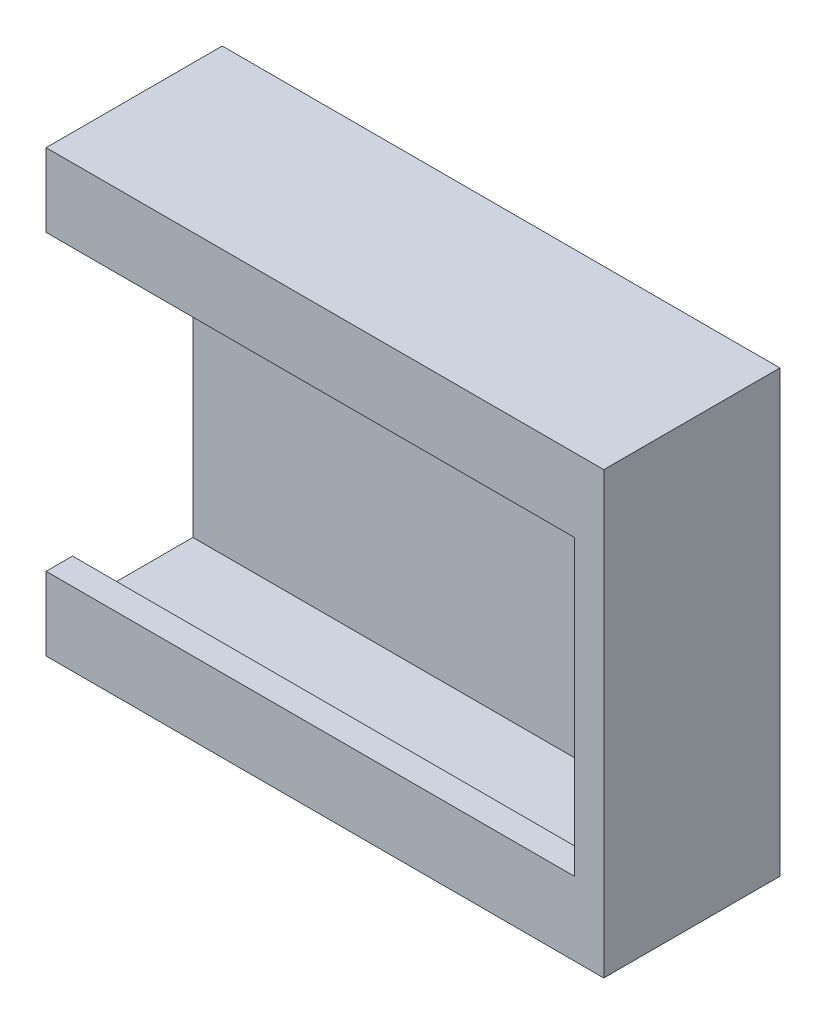
SolidWorks part; units mm, degrees
material "Alliage 1060"
ref_plane "Plan de dessus" through (0, 0, 0) normal (0, 0, 1) x (1, 0, 0)
ref_plane "Plan de droite" through (0, 0, 0) normal (0, 1, 0) x (1, 0, 0)
ref_plane "Plan de face" through (0, 0, 0) normal (1, 0, 0) x (0, 0, -1)
sketch "Esquisse1" plane through (0, 0, 0) normal (0, 0, 1) x (1, 0, 0)
  line L1 (0, 0) -> (95, 0)
  line L2 (0, 0) -> (0, 75)
  line L3 (0, 75) -> (95, 75)
  line L4 (95, 0) -> (95, 75)
  dimension "D1" = 75
  dimension "D2" = 95
extrude "Boss.-Extru.1" add sketch "Esquisse1" along normal blind 5
sketch "Esquisse2" plane through (0, 0, 5) normal (0, 0, 1) x (1, 0, 0)
  line L3 (0, 70) -> (0, 75)
  line L4 (0, 75) -> (95, 75)
  line L5 (95, 75) -> (95, 0)
  line L6 (0, 5) -> (90, 5)
  line L7 (90, 5) -> (90, 70)
  line L8 (90, 70) -> (0, 70)
  line L9 (0, 5) -> (90, 5)
  line L10 (90, 5) -> (90, 70)
  line L11 (90, 70) -> (0, 70)
  line L12 (95, 0) -> (0, 0)
  line L13 (0, 0) -> (0, 5)
  dimension "D1" = 5
extrude "Boss.-Extru.2" add sketch "Esquisse2" along normal blind 25
sketch "Esquisse3" plane through (90, 0, 0) normal (-1, 0, 0) x (0, 0, 1)
  line L1 (30, 70) -> (30, 5) construction
  line L8 (30, 70) -> (25.5, 70)
  line L9 (30, 70) -> (5, 70) construction
  line L10 (25.5, 70) -> (25.5, 62.5)
  line L11 (30, 37.5) -> (5, 37.5) construction
  line L12 (5, 70) -> (5, 5) construction
  line L13 (25.5, 5) -> (25.5, 12.5)
  line L14 (30, 5) -> (25.5, 5)
  line L21 (30, 70) -> (30, 62.5)
  line L22 (30, 62.5) -> (25.5, 62.5)
  line L23 (30, 5) -> (30, 12.5)
  line L24 (30, 12.5) -> (25.5, 12.5)
  dimension "D1" = 7.5
  dimension "D3" = 4.5
extrude "Boss.-Extru.3" add sketch "Esquisse3" along normal up to surface (90 mm away) up to face at (0, 37.5, 16.25)
